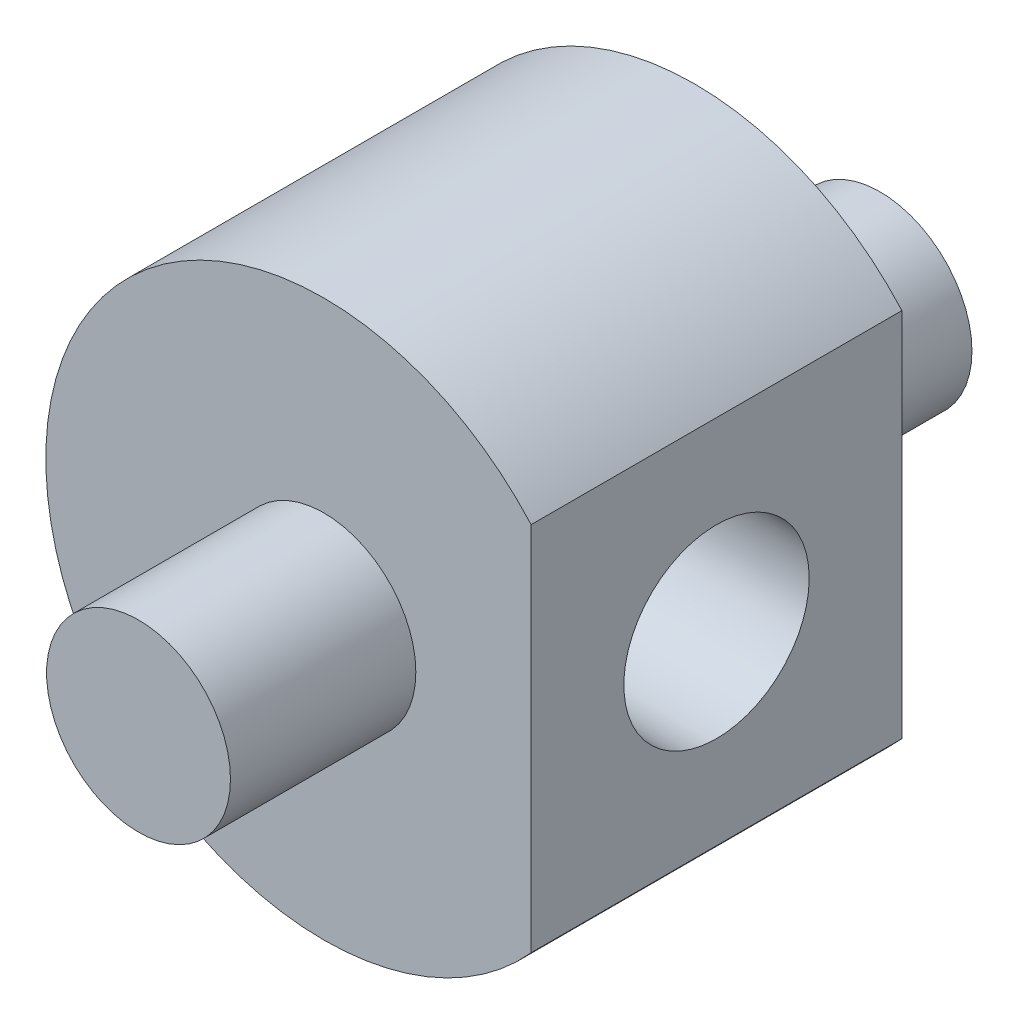
SolidWorks part; units mm, degrees
ref_plane "Front Plane" through (0, 0, 0) normal (0, 0, 1) x (1, 0, 0)
ref_plane "Top Plane" through (0, 0, 0) normal (0, 1, 0) x (1, 0, 0)
ref_plane "Right Plane" through (0, 0, 0) normal (1, 0, 0) x (0, 0, -1)
sketch "Sketch1" plane through (0, 0, 0) normal (0, 0, 1) x (1, 0, 0)
  line L0 (0, 0) -> (0, 12.7)
  arc A0 (0, 0) -> (0, 12.7) centre (-7.0995, 6.35) cw
  dimension "D2" = 19.05
  dimension "D1" = 12.7
extrude "Boss-Extrude1" add sketch "Sketch1" along normal blind 12.7
sketch "Sketch3" plane through (0, 0, 12.7) normal (0, 0, 1) x (1, 0, 0)
  circle A0 centre (-7.0995, 6.35) radius 3.1496
  dimension "D1" = 6.2992
extrude "Boss-Extrude2" add sketch "Sketch3" along normal blind 6.35 and the other way blind 19.05
sketch "Sketch4" plane through (0, 0, 0) normal (1, 0, 0) x (0, 0, -1)
  circle A0 centre (-6.35, 6.35) radius 3.175
  dimension "D1" = 6.35
extrude "Cut-Extrude1" cut sketch "Sketch4" against normal through all
